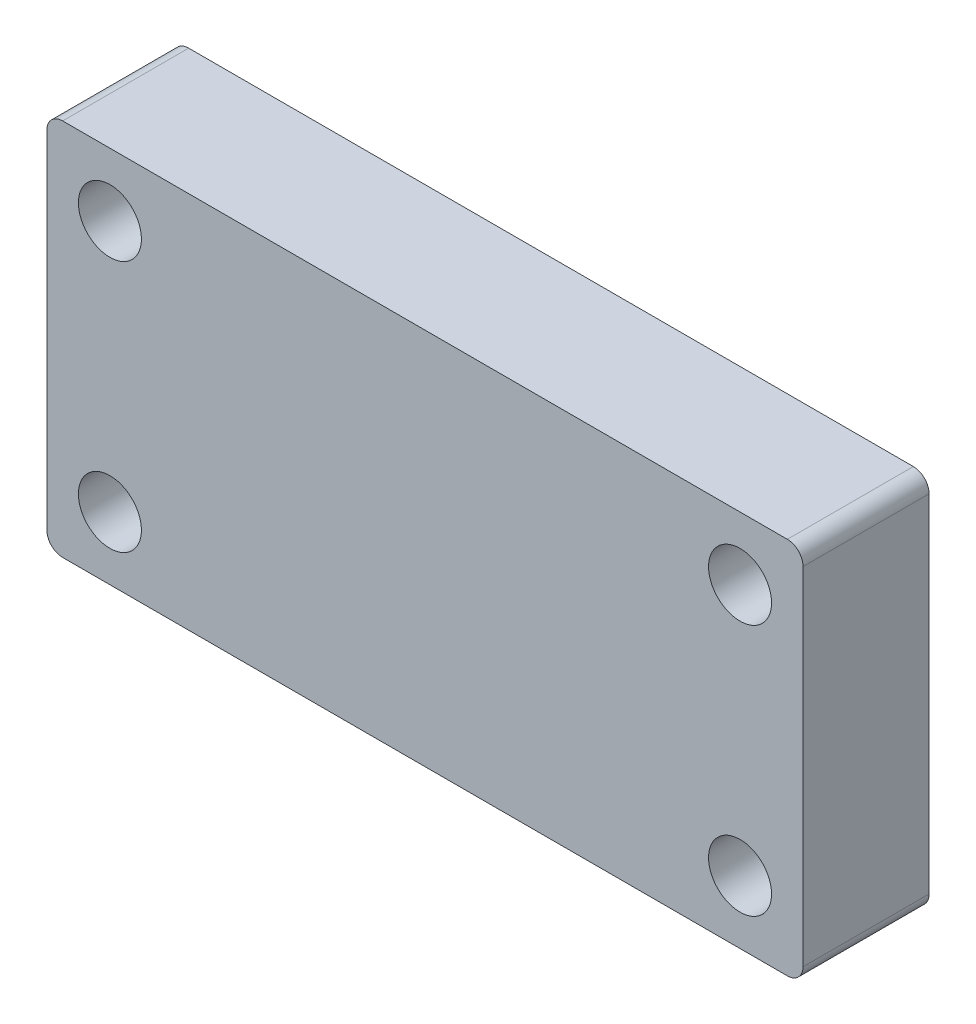
SolidWorks part; units mm, degrees
ref_plane "Front Plane" through (0, 0, 0) normal (0, 0, 1) x (1, 0, 0)
ref_plane "Top Plane" through (0, 0, 0) normal (0, 1, 0) x (1, 0, 0)
ref_plane "Right Plane" through (0, 0, 0) normal (1, 0, 0) x (0, 0, -1)
sketch "Sketch2" plane through (0, 0, 0) normal (0, 0, 1) x (1, 0, 0)
  line L1 (-9.525, 4.7625) -> (9.525, 4.7625)
  line L2 (-9.525, 4.7625) -> (-9.525, -4.7625)
  line L3 (-9.525, -4.7625) -> (9.525, -4.7625)
  line L4 (9.525, 4.7625) -> (9.525, -4.7625)
  line L5 (-9.525, 4.7625) -> (9.525, -4.7625) construction
  line L6 (-9.525, -4.7625) -> (9.525, 4.7625) construction
  point P0 (0, 0)
  dimension "D1" = 19.05
  dimension "D2" = 9.525
extrude "Boss-Extrude1" add sketch "Sketch2" along normal blind 3.175
sketch "Sketch3" plane through (0, 0, 3.175) normal (0, 0, 1) x (1, 0, 0)
  line L0 (0, 4.7625) -> (0, -4.7625) construction
  line L1 (9.525, 4.7625) -> (-9.525, 4.7625) construction
  line L2 (-9.525, -4.7625) -> (9.525, -4.7625) construction
  line L3 (-9.525, 0) -> (9.525, 0) construction
  line L4 (-9.525, 4.7625) -> (-9.525, -4.7625) construction
  line L5 (9.525, -4.7625) -> (9.525, 4.7625) construction
  circle A0 centre (-7.9375, 3.175) radius 0.7938
  circle A1 centre (-7.9375, -3.175) radius 0.7938
  circle A2 centre (7.9375, -3.175) radius 0.7937
  circle A3 centre (7.9375, 3.175) radius 0.7937
  point P14 (-7.9468, 3.4581)
  dimension "D1" = 1.5875
  dimension "D2" = 1.5875
  dimension "D3" = 1.5875
extrude "Cut-Extrude1" cut sketch "Sketch3" against normal through all
fillet "Fillet1" radius 0.3969 4 edges at (9.525, -4.7625, 1.5875) (-9.525, -4.7625, 1.5875) (-9.525, 4.7625, 1.5875) (9.525, 4.7625, 1.5875)
